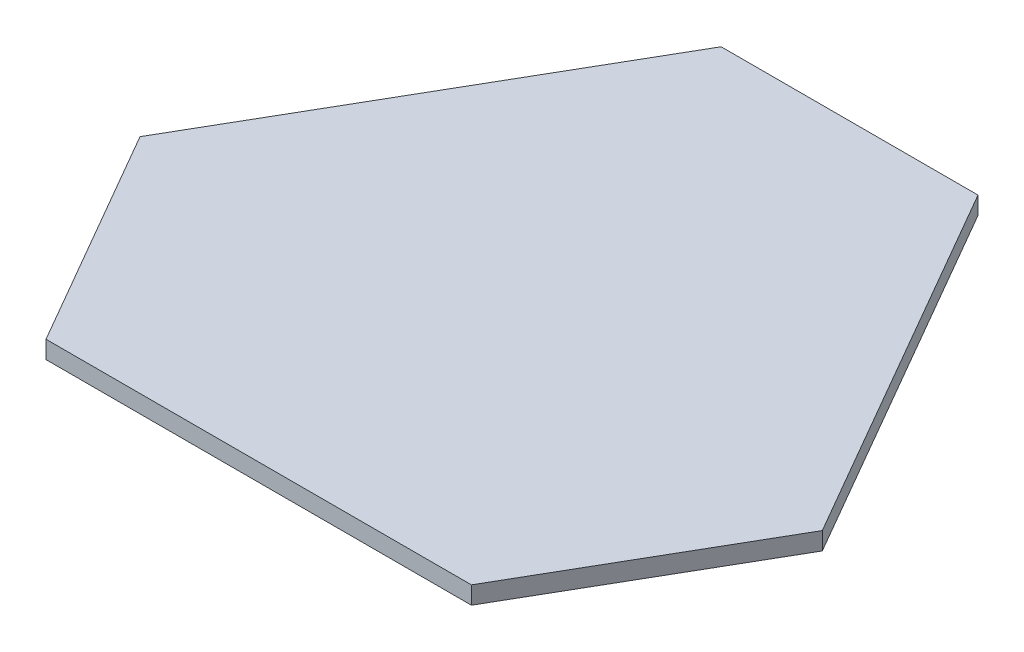
SolidWorks part; units mm, degrees
ref_plane "Front Plane" through (0, 0, 0) normal (0, 0, 1) x (1, 0, 0)
ref_plane "Top Plane" through (0, 0, 0) normal (0, 1, 0) x (1, 0, 0)
ref_plane "Right Plane" through (0, 0, 0) normal (1, 0, 0) x (0, 0, -1)
sketch "Sketch1" plane through (0, 0, 0) normal (0, 1, 0) x (1, 0, 0)
  line L0 (-80, 184.0608) -> (80, 184.0608)
  line L1 (80, 184.0608) -> (212.5, -45.4359)
  line L2 (212.5, -45.4359) -> (132.5, -184)
  line L3 (132.5, -184) -> (-132.5, -184)
  line L4 (-132.5, -184) -> (-212.5, -45.4359)
  line L5 (-212.5, -45.4359) -> (-80, 184.0608)
  dimension "D1" = 60
  dimension "D2" = 60
  dimension "D3" = 160
  dimension "D4" = 160
  dimension "D5" = 160
  dimension "D6" = 265
  dimension "D7" = 265
  dimension "D8" = 265
  dimension "D9" = 212.5
  dimension "D10" = 184
extrude "Boss-Extrude1" add sketch "Sketch1" along normal blind 11
